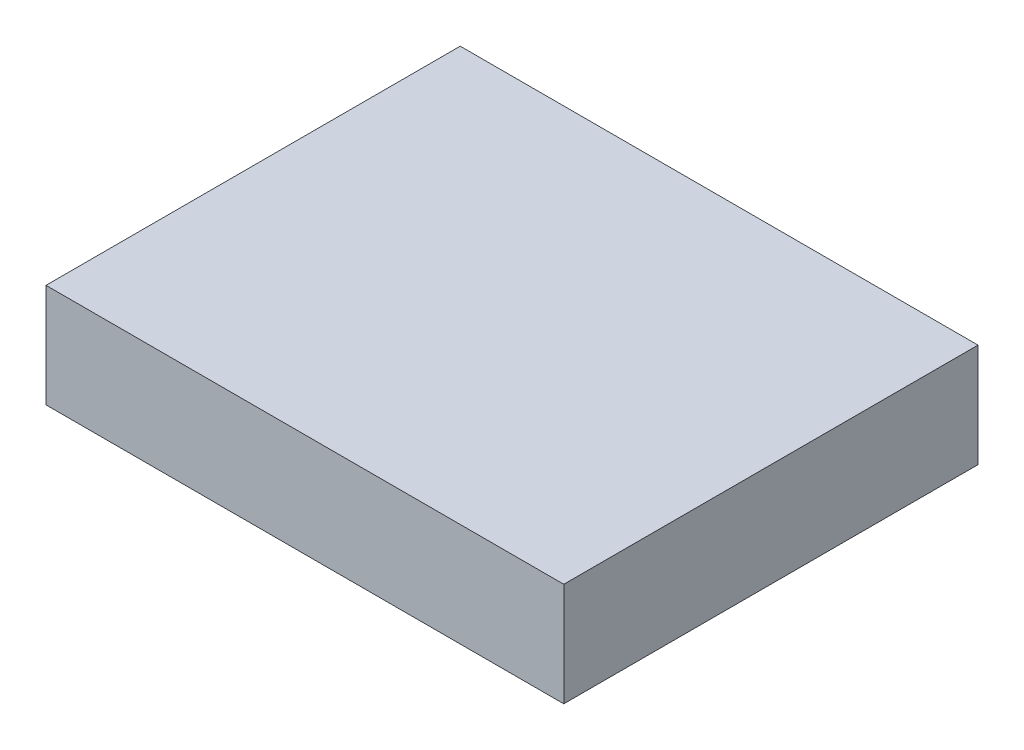
SolidWorks part; units mm, degrees
ref_plane "Front Plane" through (0, 0, 0) normal (0, 0, 1) x (1, 0, 0)
ref_plane "Top Plane" through (0, 0, 0) normal (0, 1, 0) x (1, 0, 0)
ref_plane "Right Plane" through (0, 0, 0) normal (1, 0, 0) x (0, 0, -1)
sketch "Sketch1" plane through (0, 0, 0) normal (0, 1, 0) x (1, 0, 0)
  line L1 (0, 0) -> (-15, 0)
  line L2 (0, 0) -> (0, -12)
  line L3 (0, -12) -> (-15, -12)
  line L4 (-15, 0) -> (-15, -12)
  dimension "D1" = 15
  dimension "D2" = 12
extrude "Boss-Extrude1" add sketch "Sketch1" along normal blind 3
equation "\"largo\"=1.5"
equation "\"D1@Sketch1\"=\"largo\""
equation "\"ancho\"=1.2"
equation "\"D2@Sketch1\"=\"ancho\""
equation "\"alto\"=0.3"
equation "\"D1@Boss-Extrude1\"=\"alto\""
